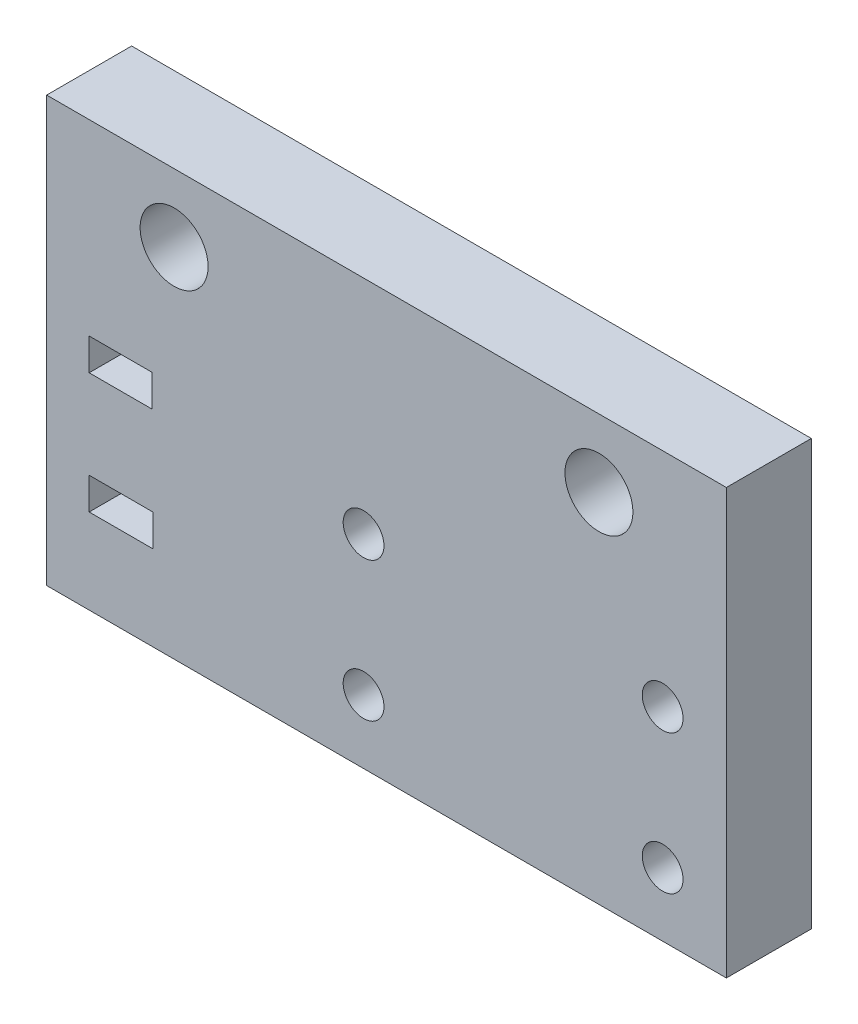
SolidWorks part; units mm, degrees
ref_plane "Front Plane" through (0, 0, 0) normal (0, 0, 1) x (1, 0, 0)
ref_plane "Top Plane" through (0, 0, 0) normal (0, 1, 0) x (1, 0, 0)
ref_plane "Right Plane" through (0, 0, 0) normal (1, 0, 0) x (0, 0, -1)
sketch "Sketch1" plane through (0, 0, 0) normal (0, 0, 1) x (1, 0, 0)
  line L1 (-57.8461, 15.6983) -> (-7.0461, 15.6983)
  line L2 (-57.8461, 15.6983) -> (-57.8461, -41.4517)
  line L3 (-57.8461, -41.4517) -> (-7.0461, -41.4517)
  line L4 (-7.0461, 15.6983) -> (-7.0461, -41.4517)
  dimension "D1" = 50.8
  dimension "D2" = 57.15
extrude "Boss-Extrude1" add sketch "Sketch1" along normal blind 6.35
sketch "Sketch5" plane through (0, 0, 6.35) normal (0, 0, 1) x (1, 0, 0)
  line L0 (-7.0461, -41.4517) -> (-7.0461, 15.6983) construction
  line L1 (-57.8461, -41.4517) -> (-7.0461, -41.4517) construction
  line L2 (-7.0461, 15.6983) -> (-57.8461, 15.6983) construction
  line L3 (-57.8461, 15.6983) -> (-57.8461, -41.4517) construction
  circle A0 centre (-11.8086, -26.2752) radius 1.524
  circle A1 centre (-11.8086, -36.6892) radius 1.524
  circle A2 centre (-34.1606, -26.2752) radius 1.524
  circle A3 centre (-34.1606, -36.6892) radius 1.524
  circle A4 centre (-48.3211, 10.6183) radius 2.54
  circle A5 centre (-16.5711, 10.6183) radius 2.54
  circle A6 centre (-48.3211, -2.0817) radius 2.54
  circle A7 centre (-16.5711, -2.0817) radius 2.54
  circle A8 centre (-48.3211, -14.7817) radius 2.54
  circle A9 centre (-16.5711, -14.7817) radius 2.54
  dimension "D1" = 4.7625
  dimension "D3" = 10.414
  dimension "D5" = 5.08
  dimension "D6" = 9.525
  dimension "D7" = 9.525
  dimension "D9" = 5.08
  dimension "D2" = 4.7625
  dimension "D4" = 22.352
  dimension "D8" = 3
extrude "Cut-Extrude1" cut sketch "Sketch5" against normal through all
sketch "Sketch6" plane through (0, 0, 6.35) normal (0, 0, 1) x (1, 0, 0)
  line L0 (-57.8461, 15.6983) -> (-57.8461, -41.4517) construction
  line L1 (-54.6711, -32.7205) -> (-49.9086, -32.7205)
  line L2 (-54.6711, -32.7205) -> (-54.6711, -35.1017)
  line L3 (-54.6711, -35.1017) -> (-49.9086, -35.1017)
  line L4 (-49.9086, -32.7205) -> (-49.9086, -35.1017)
  line L5 (-57.8461, -41.4517) -> (-7.0461, -41.4517) construction
  line L6 (-54.6711, -23.7096) -> (-49.9701, -23.7096)
  line L7 (-54.6711, -23.7096) -> (-54.6711, -26.0908)
  line L8 (-54.6711, -26.0908) -> (-49.9701, -26.0908)
  line L9 (-49.9701, -23.7096) -> (-49.9701, -26.0908)
  dimension "D1" = 4.7625
  dimension "D2" = 2.3813
  dimension "D3" = 3.175
  dimension "D4" = 6.35
  dimension "D5" = 6.6297
  dimension "D6" = 6.6297
  dimension "D7" = 3.175
extrude "Cut-Extrude2" cut sketch "Sketch6" against normal through all
sketch "Sketch7" plane through (0, 0, 6.35) normal (0, 0, 1) x (1, 0, 0)
  line L0 (-7.0461, -41.4517) -> (-7.0461, 15.6983) construction
  line L1 (-7.0461, -9.7017) -> (-57.8461, -9.7017)
  line L2 (-7.0461, -9.7017) -> (-7.0461, 15.6983)
  line L3 (-7.0461, 15.6983) -> (-57.8461, 15.6983)
  line L4 (-57.8461, -9.7017) -> (-57.8461, 15.6983)
  dimension "D1" = 25.4
extrude "Cut-Extrude3" cut sketch "Sketch7" against normal through all
